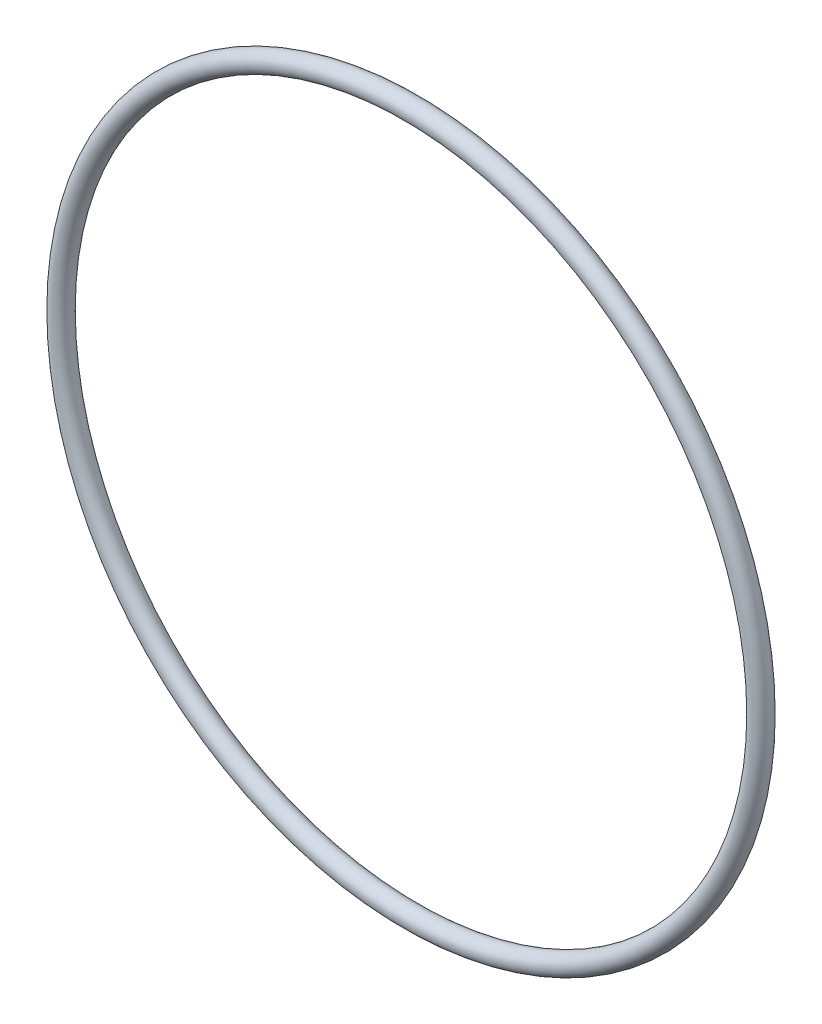
SolidWorks part; units mm, degrees
ref_plane "Front Plane" through (0, 0, 0) normal (0, 0, 1) x (1, 0, 0)
ref_plane "Top Plane" through (0, 0, 0) normal (0, 1, 0) x (1, 0, 0)
ref_plane "Right Plane" through (0, 0, 0) normal (1, 0, 0) x (0, 0, -1)
sketch "Sketch1" plane through (0, 0, 0) normal (0, 0, 1) x (1, 0, 0)
  circle A0 centre (0, 0) radius 55.245
  dimension "D1" = 110.49
sweep "Base-Sweep" add path "Sketch1" circular profile diameter 3.175 parameters "D3"=3.175
